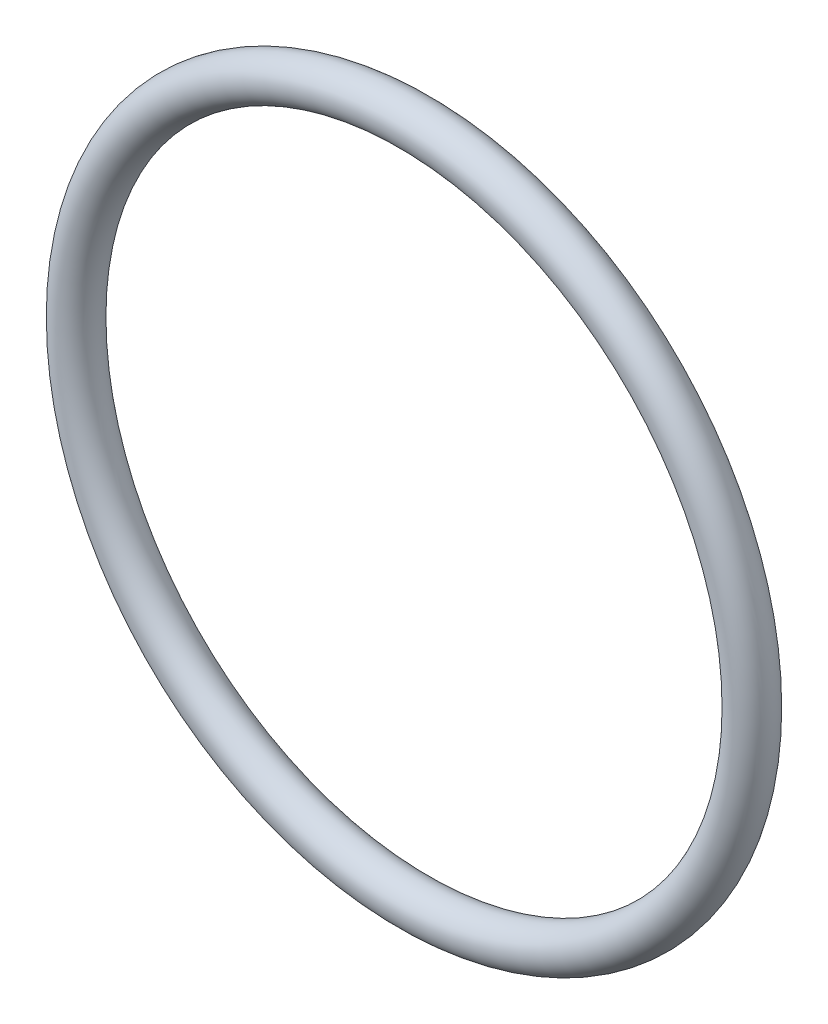
SolidWorks part; units mm, degrees
ref_plane "Front" through (0, 0, 0) normal (0, 0, 1) x (1, 0, 0)
ref_plane "Top" through (0, 0, 0) normal (0, 1, 0) x (1, 0, 0)
ref_plane "Right" through (0, 0, 0) normal (1, 0, 0) x (0, 0, -1)
sketch "Sketch1" plane through (0, 0, 0) normal (1, 0, 0) x (0, -1, 0)
  line L0 (0, -0.889) -> (0, 0.889) construction
  line L2 (-15.7721, 0) -> (15.7721, 0) construction
  line L3 (-13.3477, 0) -> (13.3477, 0) construction
  circle A0 centre (14.2367, 0) radius 0.889
  point P9 (13.3477, 0)
  point P10 (15.1257, 0)
  point P13 (14.2367, 0.889)
  point P14 (14.2367, -0.889)
  dimension "Width" = 1.778
  dimension "ID" = 26.6954
revolve "Revolve1" add sketch "Sketch1" angle 360 about L0
